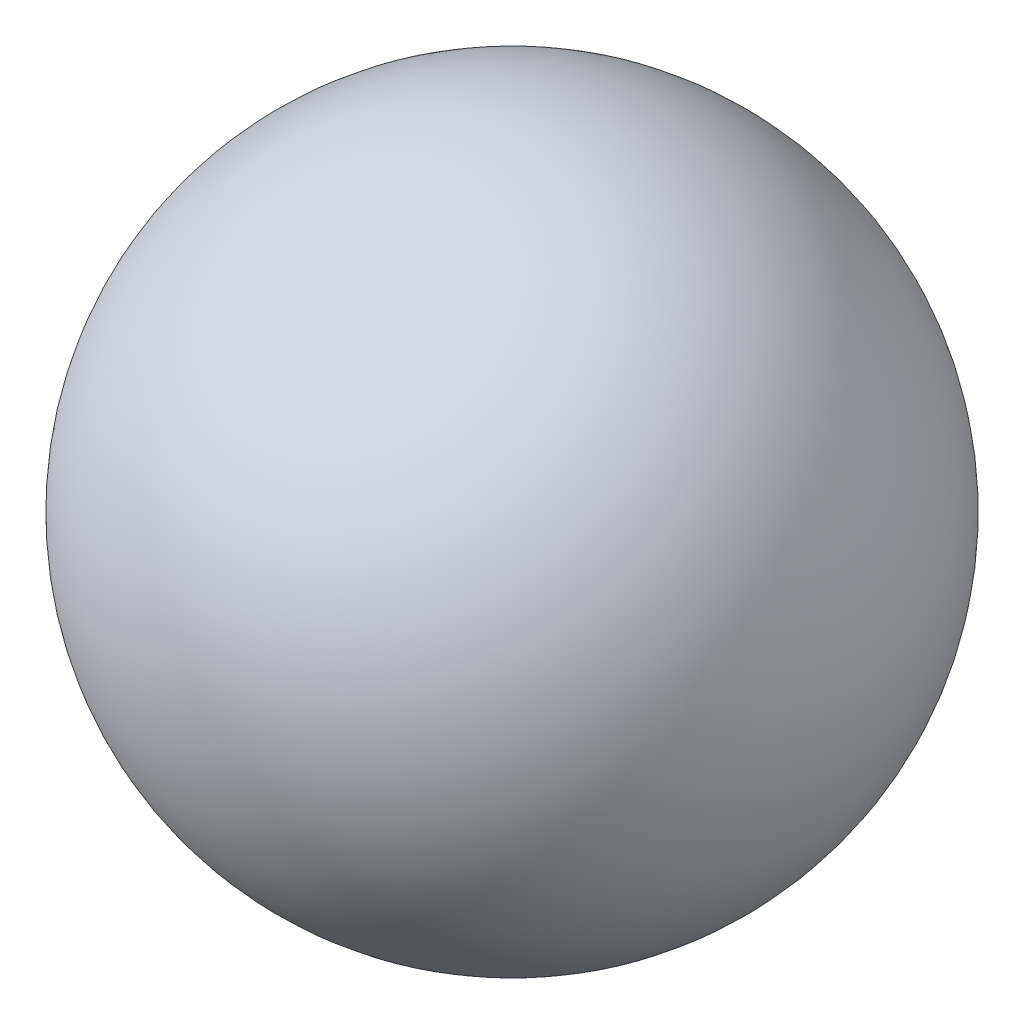
SolidWorks part; units mm, degrees
ref_plane "Plan de face" through (0, 0, 0) normal (0, 0, 1) x (1, 0, 0)
ref_plane "Plan de dessus" through (0, 0, 0) normal (0, 1, 0) x (1, 0, 0)
ref_plane "Plan de droite" through (0, 0, 0) normal (1, 0, 0) x (0, 0, -1)
sketch "Esquisse1" plane through (0, 0, 0) normal (0, 0, 1) x (1, 0, 0)
  line L1 (0, 11.5) -> (0, -11.5)
  arc A1 (0, 11.5) -> (0, -11.5) centre (0, 0) ccw
  dimension "D1" = 11.5
revolve "Révolution4" add sketch "Esquisse1" angle 360 about L1
